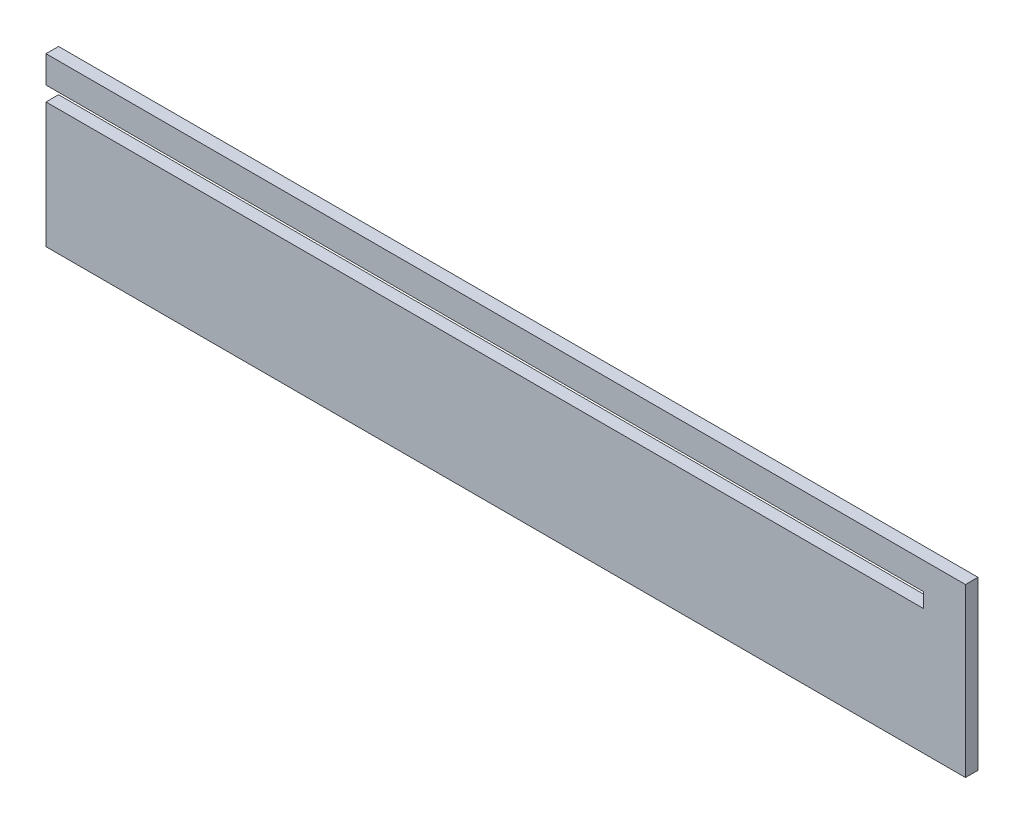
SolidWorks part; units mm, degrees
ref_plane "Přední rovina" through (0, 0, 0) normal (0, 0, 1) x (1, 0, 0)
ref_plane "Horní rovina" through (0, 0, 0) normal (0, 1, 0) x (1, 0, 0)
ref_plane "Pravá rovina" through (0, 0, 0) normal (1, 0, 0) x (0, 0, -1)
sketch "Skica1" plane through (0, 0, 0) normal (0, 0, 1) x (1, 0, 0)
  line L1 (0, 0) -> (220, 0)
  line L2 (0, 0) -> (0, 40)
  line L3 (0, 40) -> (220, 40)
  line L4 (220, 0) -> (220, 40)
  line L5 (0, 33.5) -> (210, 33.5)
  line L6 (0, 33.5) -> (0, 30)
  line L7 (0, 30) -> (210, 30)
  line L8 (210, 33.5) -> (210, 30)
  dimension "D1" = 40
  dimension "D2" = 220
  dimension "D3" = 3.5
  dimension "D4" = 210
  dimension "D5" = 6.5
extrude "Přidat vysunutím1" add sketch "Skica1" along normal blind 3 contours L5 L8 L7 L2 L1 L4 L3
